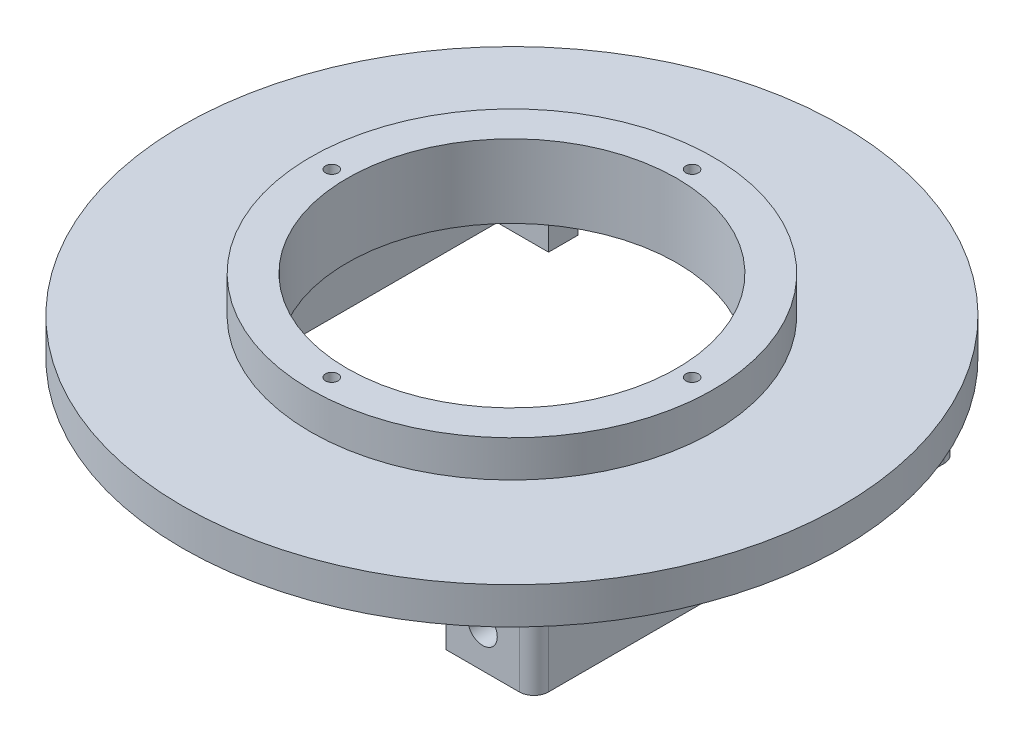
SolidWorks part; units mm, degrees
ref_plane "前视" through (0, 0, 0) normal (0, 0, 1) x (1, 0, 0)
ref_plane "上视" through (0, 0, 0) normal (0, 1, 0) x (1, 0, 0)
ref_plane "右视" through (0, 0, 0) normal (1, 0, 0) x (0, 0, -1)
sketch "草图2" plane through (0, 0, 0) normal (0, 1, 0) x (1, 0, 0)
  circle A0 centre (0, 0) radius 22.5
  circle A1 centre (0, 0) radius 45
  dimension "D1" = 45
  dimension "D2" = 90
extrude "凸台-拉伸1" add sketch "草图2" along normal blind 5
sketch "草图3" plane through (0, 0, 0) normal (0, -1, 0) x (1, 0, 0)
  line L0 (-42.2776, 0) -> (44.9986, 0) construction
  line L1 (0, 41.3309) -> (0, -46.6494) construction
  line L2 (-27, 25) -> (-27, -25)
  line L3 (20, -29) -> (20, -25)
  line L4 (-32, 25) -> (-32, -25)
  line L5 (32, -29) -> (20, -29)
  line L6 (-32, -25) -> (-32, -29)
  line L7 (-32, -29) -> (-20, -29)
  line L8 (-20, -29) -> (-20, -25)
  line L9 (-20, -25) -> (-27, -25)
  line L10 (-32, 29) -> (-20, 29)
  line L11 (-32, 25) -> (-32, 29)
  line L12 (-20, 29) -> (-20, 25)
  line L13 (-20, 25) -> (-27, 25)
  line L14 (32, -25) -> (32, -29)
  line L15 (27, 25) -> (27, -25)
  line L16 (20, -25) -> (27, -25)
  line L17 (20, 25) -> (27, 25)
  line L18 (32, 25) -> (32, -25)
  line L19 (32, 25) -> (32, 29)
  line L20 (20, 29) -> (20, 25)
  line L21 (32, 29) -> (20, 29)
  dimension "D1" = 27
  dimension "D2" = 50
  dimension "D4" = 5
  dimension "D5" = 4
  dimension "D6" = 12
extrude "凸台-拉伸2" add sketch "草图3" along normal blind 10
fillet "圆角1" radius 2 4 edges at (-32, -5, -29) (32, -5, -29) (32, -5, 29) (-32, -5, 29)
sketch "草图4" plane through (0, 0, 29) normal (0, 0, 1) x (1, 0, 0)
  line L0 (0, 13.7146) -> (0, -21.0471) construction
  line L1 (-20, -10) -> (-30, -10) construction
  line L2 (-20, -10) -> (-20, 0) construction
  circle A0 centre (-25, -5) radius 2
  circle A1 centre (25, -5) radius 2
  dimension "D3" = 4
  dimension "D1" = 5
  dimension "D2" = 5
extrude "切除-拉伸1" cut sketch "草图4" against normal through all
sketch "草图5" plane through (0, 5, 0) normal (0, 1, 0) x (1, 0, 0)
  circle A0 centre (0, 0) radius 27.5
  circle A1 centre (0, 0) radius 22.5
  dimension "D1" = 55
extrude "凸台-拉伸3" add sketch "草图5" along normal blind 5
sketch "草图6" plane through (0, 10, 0) normal (0, 1, 0) x (1, 0, 0)
  line L0 (0, 30.5024) -> (0, -29.0273) construction
  circle A0 centre (0, 24.6) radius 0.85
  circle A1 centre (24.6, 0) radius 0.85
  circle A2 centre (0, -24.6) radius 0.85
  circle A3 centre (-24.6, 0) radius 0.85
  point P15 (0, 0)
  dimension "D1" = 1.7
  dimension "D2" = 24.6
  dimension "D3" = 4
extrude "切除-拉伸2" cut sketch "草图6" against normal through all
